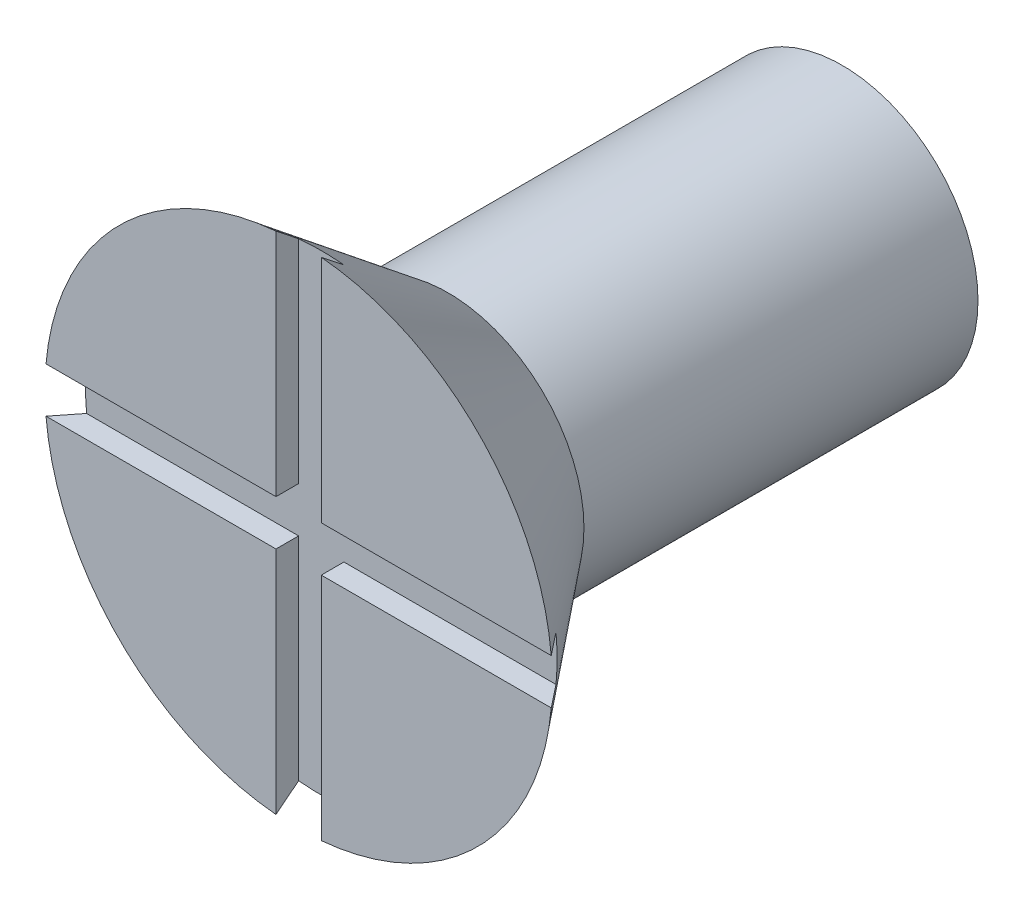
SolidWorks part; units mm, degrees
material "6061 Alloy"
ref_plane "Front Plane" through (0, 0, 0) normal (0, 0, 1) x (1, 0, 0)
ref_plane "Top Plane" through (0, 0, 0) normal (0, 1, 0) x (1, 0, 0)
ref_plane "Right Plane" through (0, 0, 0) normal (1, 0, 0) x (0, 0, -1)
sketch "Sketch2" plane through (0, 0, 0) normal (1, 0, 0) x (0, 0, -1)
  line L0 (0, 0) -> (0, 2.8)
  line L1 (0, 0) -> (1.65, 0) construction
  line L2 (1.65, 0) -> (1.65, 1.5) construction
  line L3 (0, 2.8) -> (1.65, 1.5)
  line L4 (1.65, 1.5) -> (6, 1.5)
  line L5 (6, 1.5) -> (6, 0)
  line L6 (0, 0) -> (6, 0)
  line L7 (6, 0) -> (1.65, 0) construction
  dimension "D1" = 2.8
  dimension "D2" = 1.65
  dimension "D3" = 1.5
  dimension "D4" = 4.35
revolve "Revolve1" add sketch "Sketch2" angle 360 about L6
sketch "Sketch3" plane through (0, 0, 0) normal (0, 0, 1) x (1, 0, 0)
  line L0 (-0.25, 0) -> (0, 0) construction
  line L1 (0, 2.8) -> (0, -0.25) construction
  line L2 (-0.25, 2.8) -> (-0.25, 0.25)
  line L3 (0.25, 2.8) -> (0.25, 0.25)
  line L4 (-2.8, -0.25) -> (-0.25, -0.25)
  line L5 (-2.8, 0.25) -> (-0.25, 0.25)
  line L6 (-0.25, 2.8) -> (0, 3.1032)
  line L7 (0, 3.1032) -> (0.25, 2.8)
  line L8 (2.8, 0.25) -> (3.2111, 0)
  line L9 (3.2111, 0) -> (2.8, -0.25)
  line L10 (-2.8, 0.25) -> (-3.2561, -0.0273)
  line L11 (-3.2561, -0.0273) -> (-2.8, -0.25)
  line L12 (-0.25, -2.8) -> (0.125, -3.4167)
  line L13 (0.125, -3.4167) -> (0.25, -2.8)
  line L14 (0.25, 0.25) -> (2.8, 0.25)
  line L15 (-2.8, 0.25) -> (2.8, 0.25) construction
  line L16 (-0.25, -0.25) -> (-0.25, -2.8)
  line L17 (-0.25, 2.8) -> (-0.25, -2.8) construction
  line L18 (-2.8, 0) -> (2.8, 0) construction
  line L19 (0.25, -0.25) -> (2.8, -0.25)
  line L20 (-2.8, -0.25) -> (2.8, -0.25) construction
  line L21 (0, 2.8) -> (0, -2.8) construction
  line L22 (0.25, 0) -> (2.8, 0) construction
  line L23 (0.25, -0.25) -> (0.25, -2.8)
  line L26 (0.25, 2.8) -> (0.25, -2.8) construction
  circle A1 centre (0, 0) radius 2.8 construction
  dimension "D1" = 0.25
  dimension "D2" = 0.25
  dimension "D3" = 0.25
  dimension "D4" = 0.25
extrude "Cut-Extrude1" cut sketch "Sketch3" against normal blind 0.25
